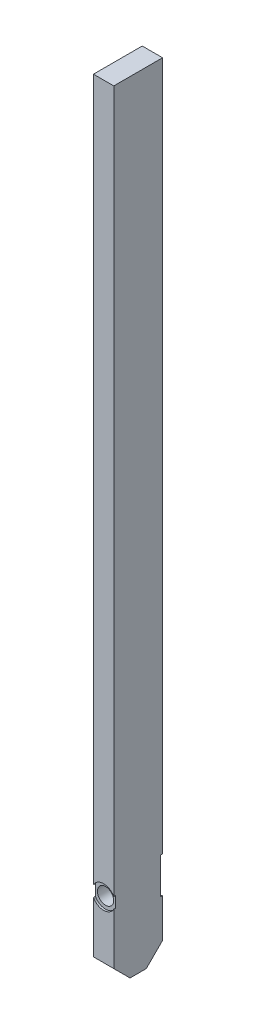
SolidWorks part; units mm, degrees
ref_plane "Front Plane" through (0, 0, 0) normal (0, 0, 1) x (1, 0, 0)
ref_plane "Top Plane" through (0, 0, 0) normal (0, 1, 0) x (1, 0, 0)
ref_plane "Right Plane" through (0, 0, 0) normal (1, 0, 0) x (0, 0, -1)
sketch "Sketch1" plane through (0, 0, 0) normal (1, 0, 0) x (0, 0, -1)
  line L1 (-19.05, 304.8) -> (19.05, 304.8)
  line L2 (-19.05, 304.8) -> (-19.05, -304.8)
  line L3 (-19.05, -304.8) -> (19.05, -304.8)
  line L4 (19.05, 304.8) -> (19.05, -304.8)
  line L5 (-19.05, 304.8) -> (19.05, -304.8) construction
  line L6 (-19.05, -304.8) -> (19.05, 304.8) construction
  point P0 (0, 0)
  dimension "D1" = 38.1
  dimension "D2" = 609.6
extrude "Boss-Extrude1" add sketch "Sketch1" along normal blind 15.875
sketch "Sketch2" plane through (0, 0, 19.05) normal (0, 0, 1) x (1, 0, 0)
  line L0 (7.9375, -247.65) -> (7.9375, -304.8) construction
  line L1 (15.875, -304.8) -> (0, -304.8) construction
  circle A0 centre (7.9375, -247.65) radius 4.7625
  dimension "D2" = 9.525
  dimension "D1" = 57.15
extrude "Cut-Extrude1" cut sketch "Sketch2" against normal through all
sketch "Sketch3" plane through (0, 0, 19.05) normal (0, 0, 1) x (1, 0, 0)
  circle A0 centre (7.9375, -247.65) radius 6.35
  dimension "D1" = 12.7
extrude "Cut-Extrude2" cut sketch "Sketch3" against normal blind 19.431
chamfer "Chamfer1" distance 12.7 angle 45 2 edges at (7.9375, -304.8, -19.05) (7.9375, -304.8, 19.05)
sketch "Sketch4" plane through (0, 0, -19.05) normal (0, 0, -1) x (-1, 0, 0)
  circle A0 centre (-7.9375, -247.65) radius 16.1925
  dimension "D1" = 32.385
extrude "Cut-Extrude3" cut sketch "Sketch4" against normal blind 1.778
sketch "Sketch5" plane through (0, 0, 19.05) normal (0, 0, 1) x (1, 0, 0)
  circle A0 centre (7.9375, -247.65) radius 9.017
  dimension "D1" = 18.034
extrude "Cut-Extrude4" cut sketch "Sketch5" against normal blind 1.524
sketch "Sketch6" plane through (0, 0, -17.272) normal (0, 0, -1) x (-1, 0, 0)
  circle A0 centre (-7.9375, -247.65) radius 12.319 construction
  circle A1 centre (-7.9375, -235.331) radius 0.762
  dimension "D1" = 24.638
  dimension "D2" = 1.524
extrude "Cut-Extrude5" cut sketch "Sketch6" against normal blind 12.7
